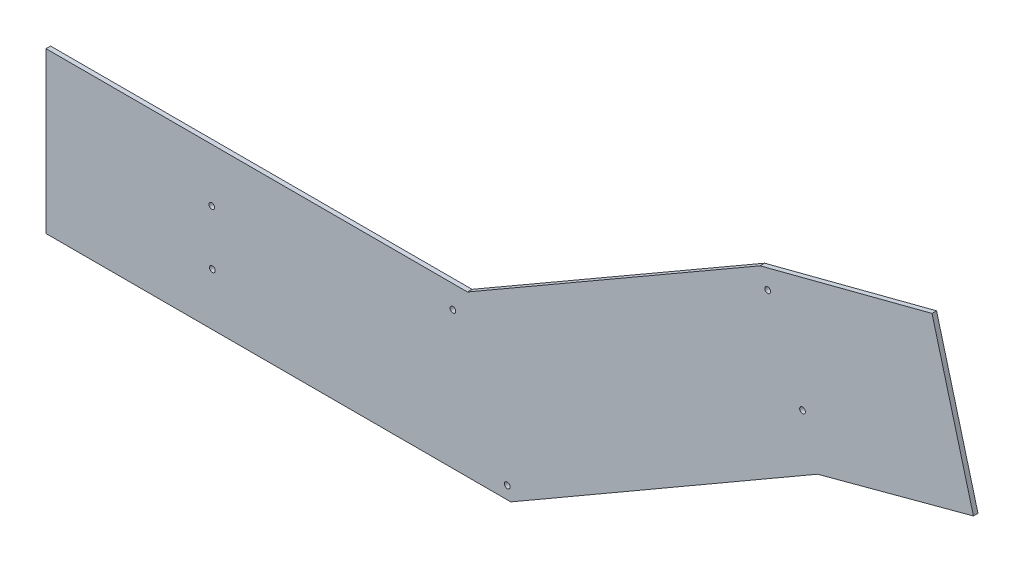
SolidWorks part; units mm, degrees
ref_plane "Plan de face" through (0, 0, 0) normal (0, 0, 1) x (1, 0, 0)
ref_plane "Plan de dessus" through (0, 0, 0) normal (0, 1, 0) x (1, 0, 0)
ref_plane "Plan de droite" through (0, 0, 0) normal (1, 0, 0) x (0, 0, -1)
sketch "Model" plane through (0, 0, 0) normal (0, 0, 1) x (1, 0, 0)
  line L0 (152.8114, 25.9717) -> (138.2826, 80.2215)
  line L1 (98.1506, 11.3316) -> (152.8114, 25.9717)
  line L2 (-9.3986, -50.8585) -> (98.1506, 11.3316)
  line L3 (-172.3739, -50.8585) -> (-9.3986, -50.8585)
  line L4 (-24.5886, 5.3017) -> (-172.3739, 5.2915)
  line L5 (138.2826, 80.2215) -> (78.0109, 64.5416)
  line L6 (-151.6088, 5.3124) -> (-151.6088, 5.2929)
  line L7 (-24.5886, 5.3017) -> (78.0109, 64.5416)
  line L8 (-172.3739, 5.3124) -> (-172.3739, -50.6876)
  line L9 (-172.3739, -50.6876) -> (-172.3739, -50.8585)
  circle A0 centre (80.6856, 58.4893) radius 1
  circle A1 centre (92.8776, 28.0855) radius 1
  circle A2 centre (-29.7028, -2.6485) radius 1
  circle A3 centre (-10.6528, -46.4381) radius 1
  circle A4 centre (-114.2594, -13.4181) radius 1
  circle A5 centre (-114.0308, -32.4935) radius 1
extrude "Boss.-Extru.1" add sketch "Model" along normal blind 1.6 contours L8 L9 L3 L2 L1 L0 L5 L7 L4 A5 A4 A3 A2 A1 A0
